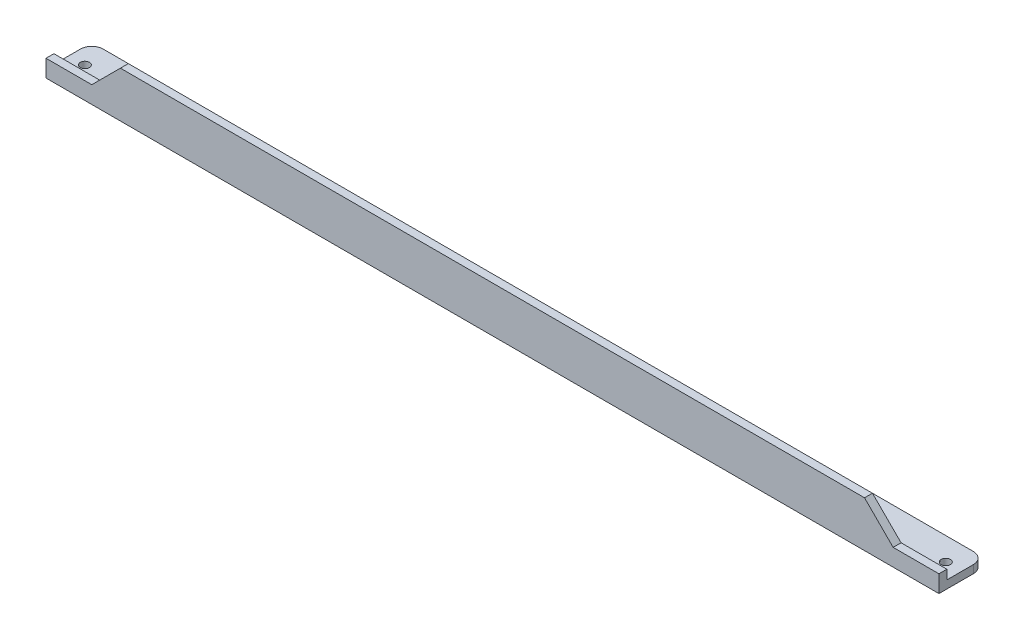
SolidWorks part; units mm, degrees
ref_plane "Front Plane" through (0, 0, 0) normal (0, 0, 1) x (1, 0, 0)
ref_plane "Top Plane" through (0, 0, 0) normal (0, 1, 0) x (1, 0, 0)
ref_plane "Right Plane" through (0, 0, 0) normal (1, 0, 0) x (0, 0, -1)
sketch "Sketch1" plane through (0, 0, 0) normal (1, 0, 0) x (0, 0, -1)
  line L0 (0, 0) -> (20, 0)
  line L1 (20, 0) -> (20, 3.4612)
  line L2 (20, 3.4612) -> (3.4612, 3.4612)
  line L3 (3.4612, 3.4612) -> (3.4612, 20)
  line L4 (3.4612, 20) -> (0, 20)
  line L5 (0, 20) -> (0, 0)
  dimension "D1" = 3.4612
  dimension "D2" = 20
extrude "Boss-Extrude1" add sketch "Sketch1" along normal blind 390
sketch "Sketch2" plane through (0, 0, 0) normal (0, -1, 0) x (1, 0, 0)
  line L0 (0, -10) -> (390, -10) construction
  line L1 (0, 0) -> (0, -20) construction
  line L2 (390, 0) -> (390, -20) construction
  circle A0 centre (195, -10) radius 2
  circle A1 centre (335, -10) radius 2
  circle A2 centre (55, -10) radius 2
  circle A3 centre (383, -10) radius 2
  circle A4 centre (7, -10) radius 2
  dimension "D1" = 4
  dimension "D2" = 140
  dimension "D3" = 140
  dimension "D4" = 48
  dimension "D5" = 48
extrude "Cut-Extrude1" cut sketch "Sketch2" against normal through all
sketch "Sketch3" plane through (0, 0, 0) normal (0, 0, 1) x (1, 0, 0)
  line L0 (0, 7.5) -> (20, 7.5)
  line L1 (0, 20) -> (0, 0) construction
  line L2 (20, 7.5) -> (32.5, 20)
  line L3 (390, 20) -> (0, 20) construction
  line L4 (195, 0) -> (195, 20) construction
  line L5 (390, 0) -> (0, 0) construction
  line L6 (0, 7.5) -> (0, 20)
  line L7 (0, 20) -> (32.5, 20)
  line L8 (390, 20) -> (357.5, 20)
  line L9 (390, 7.5) -> (390, 20)
  line L10 (370, 7.5) -> (357.5, 20)
  line L11 (390, 7.5) -> (370, 7.5)
  dimension "D1" = 45
  dimension "D2" = 7.5
  dimension "D3" = 20
extrude "Cut-Extrude2" cut sketch "Sketch3" against normal through all
fillet "Fillet1" radius 5 2 edges at (390, 1.7306, -20) (0, 1.7306, -20)
